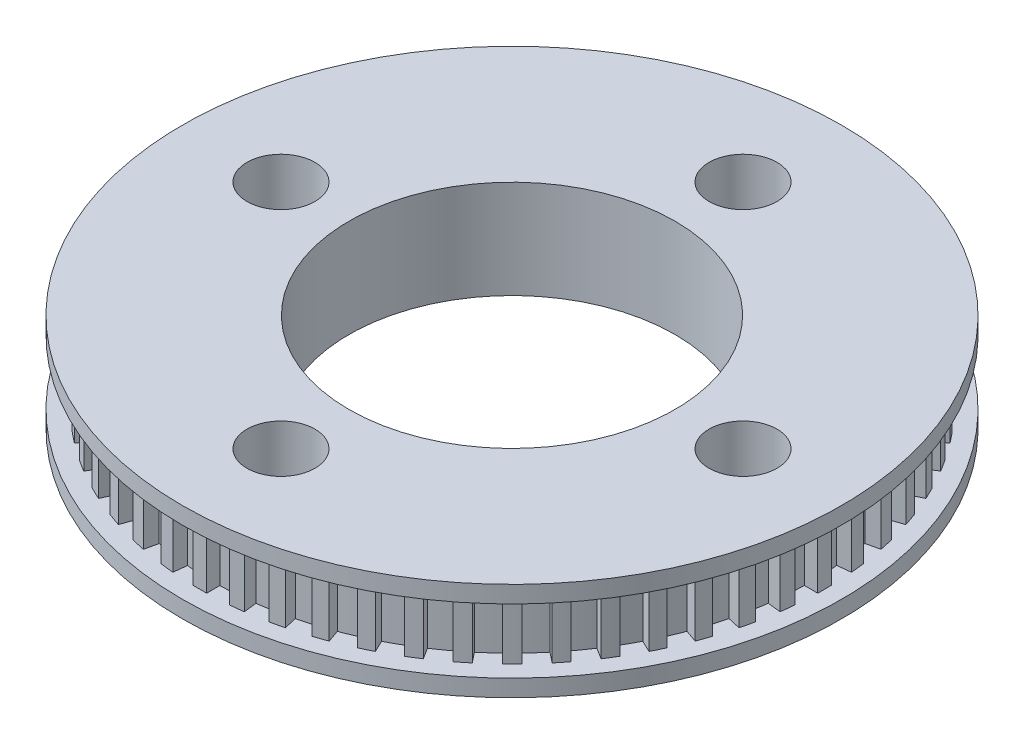
SolidWorks part; units mm, degrees
ref_plane "Front" through (0, 0, 0) normal (0, 0, 1) x (1, 0, 0)
ref_plane "Top" through (0, 0, 0) normal (0, 1, 0) x (1, 0, 0)
ref_plane "Right" through (0, 0, 0) normal (1, 0, 0) x (0, 0, -1)
sketch "Sketch1" plane through (0, 0, 0) normal (0, 1, 0) x (1, 0, 0)
  circle A0 centre (0, 0) radius 21.59 construction
  circle A1 centre (0, 0) radius 27.94
  dimension "D1" = 43.18
  dimension "D2" = 6.35
extrude "Base Extrude" add sketch "Sketch1" along normal mid plane 6
sketch "Sketch3" plane through (0, 0, 0) normal (0, 1, 0) x (1, 0, 0)
  line L0 (-0.635, 27.9328) -> (-0.635, 29.2031)
  line L1 (0.635, 27.9328) -> (0.635, 29.2031)
  circle A0 centre (0, 0) radius 27.94 construction
  arc A1 (0.635, 27.9328) -> (-0.635, 27.9328) centre (0, 0) ccw
  arc A2 (0.635, 29.2031) -> (-0.635, 29.2031) centre (0, 0) ccw
  point P4 (0, 27.94)
  dimension "D2" = 1.27
  dimension "D1" = 1.27
extrude "Tooth Extrude" add sketch "Sketch3" along normal up to surface and the other way up to surface up to face at (0, 3, 27.94) other way up to face at (0, -3, 27.94)
pattern_circular "Tooth Pattern" count 56 over 360 about axis through (0, 0, -0.0188) along (0, 1, 0) of "Tooth Extrude"
sketch "Sketch4" plane through (0, 3, 0) normal (0, 1, 0) x (1, 0, 0)
  circle A3 centre (0, 0) radius 30.7975
  arc A4 (0.635, 29.2031) -> (-0.635, 29.2031) centre (0, 0) ccw construction
  dimension "D1" = 1.5875
extrude "Belt Shield" add sketch "Sketch4" along normal blind 1.5875
mirror "Belt Shield Mirror" about plane through (0, 0, 0) normal (0, 1, 0) of "Belt Shield"
sketch "Sketch5" plane through (0, 0, 0) normal (0, 1, 0) x (1, 0, 0)
  circle A1 centre (0, 0) radius 21.59 construction
  circle A2 centre (0, 0) radius 15.24
  dimension "D1" = 43.18
  dimension "D2" = 6.35
extrude "Access Hole Cut" cut sketch "Sketch5" against normal through all both and the other way through all
sketch "Sketch2" plane through (0, 0, 0) normal (0, 1, 0) x (1, 0, 0)
  circle A0 centre (0, 0) radius 21.59 construction
  circle A1 centre (0, 21.59) radius 3.175
  dimension "D1" = 43.18
  dimension "D2" = 6.35
extrude "Fastener Hole Cut" cut sketch "Sketch2" against normal through all both and the other way through all
pattern_circular "Fastener Hole Pattern" count 4 over 360 about axis through (0, 0, 0) along (0, 1, 0) of "Fastener Hole Cut"
